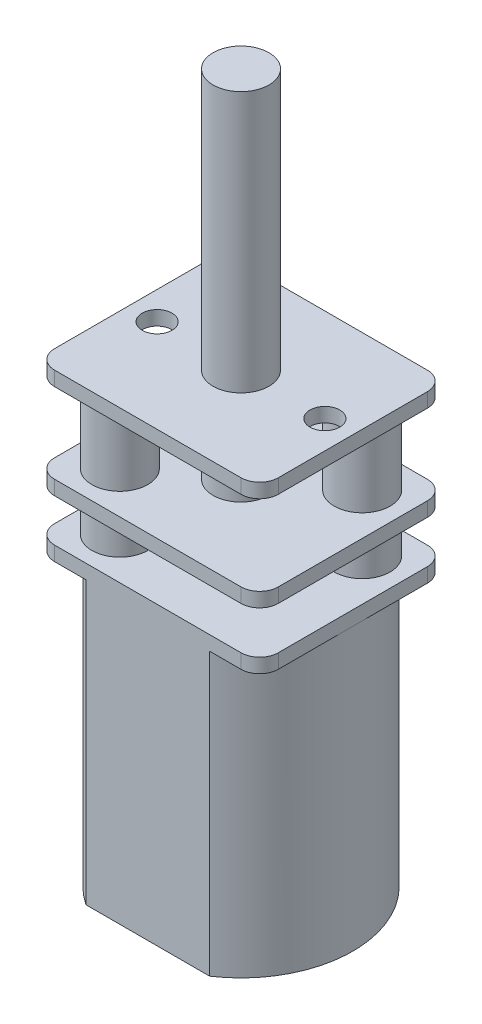
SolidWorks part; units mm, degrees
ref_plane "前视基准面" through (0, 0, 0) normal (0, 0, 1) x (1, 0, 0)
ref_plane "上视基准面" through (0, 0, 0) normal (0, 1, 0) x (1, 0, 0)
ref_plane "右视基准面" through (0, 0, 0) normal (1, 0, 0) x (0, 0, -1)
other "Configuration Table"
sketch "草图1" plane through (0, 0, 0) normal (0, 1, 0) x (1, 0, 0)
  line L1 (-6, 5) -> (6, 5)
  line L2 (-6, 5) -> (-6, -5)
  line L3 (-6, -5) -> (6, -5)
  line L4 (6, 5) -> (6, -5)
  line L5 (-6, 5) -> (6, -5) construction
  line L6 (-6, -5) -> (6, 5) construction
  point P0 (0, 0)
  dimension "D1" = 12
  dimension "D2" = 10
extrude "凸台-拉伸1" add sketch "草图1" along normal blind 24
fillet "圆角1" radius 1 4 edges at (-6, 12, -5) (6, 12, -5) (6, 12, 5) (-6, 12, 5)
sketch "草图2" plane through (0, 0, 0) normal (0, -1, 0) x (1, 0, 0)
  line L0 (-6, -4) -> (-6, 4) construction
  line L5 (-5, 5) -> (5, 5) construction
  line L6 (6, -5) -> (-6, -5)
  line L7 (6, -5) -> (6, 5)
  line L8 (6, 5) -> (-6, 5)
  line L9 (-6, -5) -> (-6, 5)
  line L10 (6, -5) -> (-6, 5) construction
  line L11 (6, 5) -> (-6, -5) construction
  circle A2 centre (0, 0) radius 6
  dimension "D1" = 0
extrude "切除-拉伸1" cut sketch "草图2" against normal offset from surface (25.67 mm away) 8.9 flip side to cut contours L6 A2 L8
sketch "草图3" plane through (0, 24, 0) normal (0, 1, 0) x (1, 0, 0)
  circle A0 centre (0, 0) radius 1.5
  dimension "D1" = 3
extrude "凸台-拉伸2" add sketch "草图3" along normal blind 14
sketch "草图5" plane through (0, 0, 0) normal (0, -1, 0) x (1, 0, 0)
  circle A0 centre (0, 0) radius 2.5
  dimension "D1" = 5
extrude "凸台-拉伸3" add sketch "草图5" along normal blind 1.25
sketch "草图6" plane through (0, 0, 0) normal (0, 0, 1) x (1, 0, 0)
  line L1 (1.5, 24) -> (1.5, 38) construction
  line L3 (1.5, 23.23) -> (1.5, 15.1)
  line L6 (1.5, 23.23) -> (21.5, 23.23)
  line L7 (1.5, 23.23) -> (1.5, 24)
  line L8 (1.5, 24) -> (21.5, 24)
  line L9 (21.5, 23.23) -> (21.5, 24)
  line L10 (1.5, 18.93) -> (21.5, 18.93)
  line L11 (1.5, 18.93) -> (1.5, 18.16)
  line L12 (1.5, 18.16) -> (21.5, 18.16)
  line L13 (21.5, 18.93) -> (21.5, 18.16)
  line L14 (21.5, 15.1) -> (1.5, 15.1)
  line L15 (21.5, 15.1) -> (21.5, 15.87)
  line L16 (21.5, 15.87) -> (1.5, 15.87)
  line L17 (1.5, 15.1) -> (1.5, 15.87)
  line L18 (21.5, 24) -> (21.5, 15.1)
  line L19 (-5, 24) -> (5, 24) construction
  line L21 (5, 15.1) -> (6, 15.1) construction
  dimension "D1" = 0.77
  dimension "D2" = 0.77
  dimension "D3" = 4.3
  dimension "D4" = 0.77
  dimension "D5" = 20
revolve "切除-旋转3" cut sketch "草图6" angle 360 about axis through (0, 38, 0) along (0, -1, 0)
sketch "草图4" plane through (0, 24, 0) normal (0, 1, 0) x (1, 0, 0)
  line L0 (0, 2.9219) -> (0, -2.4191) construction
  circle A0 centre (-4.5, 0) radius 0.8
  circle A1 centre (4.5, 0) radius 0.8
  dimension "D2" = 1.6
  dimension "D1" = 9
extrude "切除-拉伸2" cut sketch "草图4" against normal up to next
sketch "草图7" plane through (0, 24, 0) normal (0, 1, 0) x (1, 0, 0)
  line L1 (-5.25, -4.25) -> (5.25, -4.25)
  line L3 (3.75, 2.75) -> (-3.75, 2.75)
  line L4 (3.75, 2.75) -> (3.75, -2.75)
  line L5 (3.75, -2.75) -> (-3.75, -2.75)
  line L6 (-3.75, 2.75) -> (-3.75, -2.75)
  line L7 (3.75, 2.75) -> (-3.75, -2.75) construction
  line L8 (3.75, -2.75) -> (-3.75, 2.75) construction
  line L10 (-5.25, -4.25) -> (-5.25, 4.25)
  line L11 (-5.25, 4.25) -> (5.25, 4.25)
  line L12 (5.25, -4.25) -> (5.25, 4.25)
  line L13 (-5.25, -4.25) -> (5.25, 4.25) construction
  line L14 (-5.25, 4.25) -> (5.25, -4.25) construction
  circle A0 centre (-3.75, -2.75) radius 1.5
  circle A1 centre (3.75, 2.75) radius 1.5
  point P2 (0, 0)
  point P8 (0, 0)
  dimension "D1" = 3
  dimension "D3" = 8.5
  dimension "D2" = 10.5
extrude "凸台-拉伸4" add sketch "草图7" against normal up to surface (8.13 mm away) contours L4 A1 L3 | L3 A1 L4 | A0 L5 L6 | L5 A0 L6
